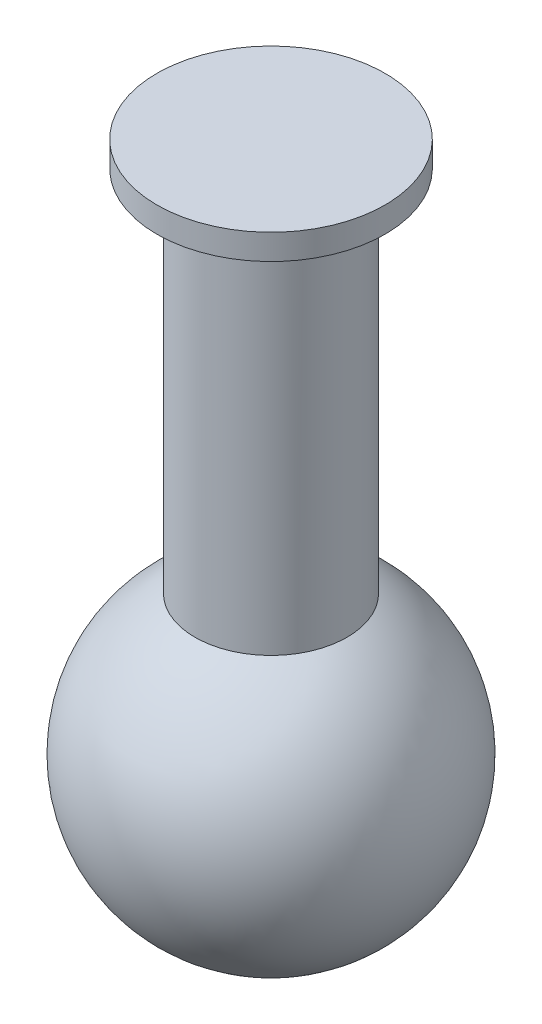
SolidWorks part; units mm, degrees
ref_plane "Front Plane" through (0, 0, 0) normal (0, 0, 1) x (1, 0, 0)
ref_plane "Top Plane" through (0, 0, 0) normal (0, 1, 0) x (1, 0, 0)
ref_plane "Right Plane" through (0, 0, 0) normal (1, 0, 0) x (0, 0, -1)
sketch "Sketch1" plane through (0, 0, 0) normal (0, 0, 1) x (1, 0, 0)
  line L0 (0, -15.875) -> (0, 15.875)
  arc A0 (0, -15.875) -> (0, 15.875) centre (0, 0) ccw
  dimension "D1" = 31.75
revolve "Revolve1" add sketch "Sketch1" angle 360 about L0
sketch "Sketch2" plane through (0, 0, 0) normal (0, 1, 0) x (1, 0, 0)
  circle A0 centre (0, 0) radius 7.62
  dimension "D1" = 15.24
extrude "Boss-Extrude1" add sketch "Sketch2" along normal blind 50.8
sketch "Sketch3" plane through (0, 50.8, 0) normal (0, 1, 0) x (1, 0, 0)
  circle A0 centre (0, 0) radius 11.43
  dimension "D1" = 22.86
extrude "Boss-Extrude2" add sketch "Sketch3" along normal blind 2.54
